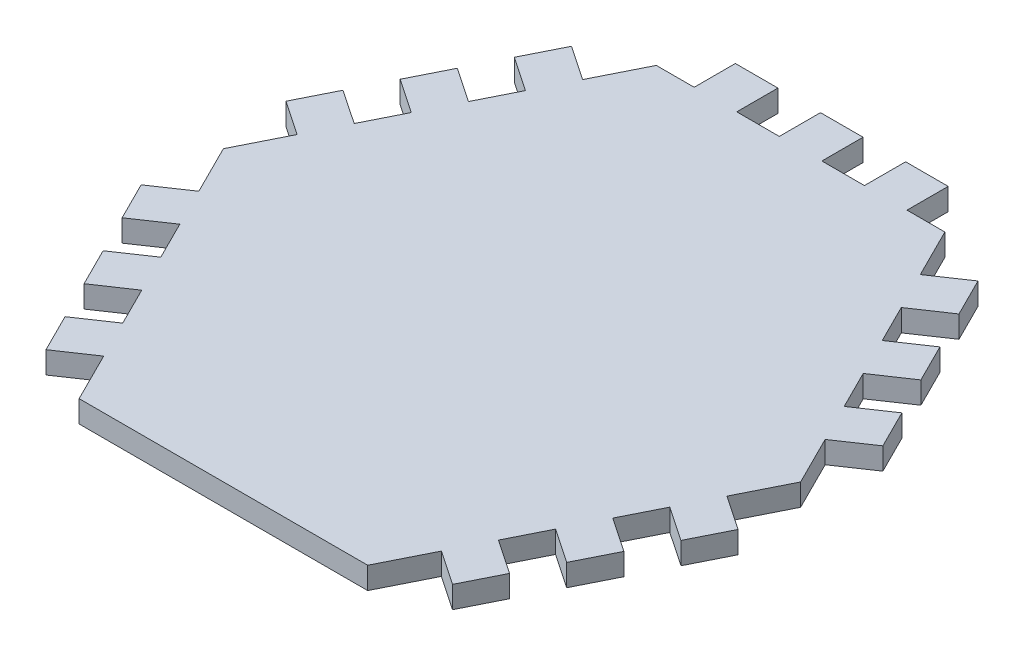
SolidWorks part; units mm, degrees
ref_plane "Front Plane" through (0, 0, 0) normal (0, 0, 1) x (1, 0, 0)
ref_plane "Top Plane" through (0, 0, 0) normal (0, 1, 0) x (1, 0, 0)
ref_plane "Right Plane" through (0, 0, 0) normal (1, 0, 0) x (0, 0, -1)
sketch "Sketch1" plane through (0, 0, 0) normal (0, 1, 0) x (1, 0, 0)
  line L0 (-36.6703, -35.293) -> (5.3697, -35.293) construction
  line L1 (5.3697, -35.293) -> (26.3947, 6.7497) construction
  line L2 (26.3947, 6.7497) -> (5.3697, 48.7923) construction
  line L3 (5.3697, 48.7923) -> (-36.6703, 48.7923) construction
  line L4 (-36.6703, 48.7923) -> (-57.6953, 6.7497) construction
  line L5 (-57.6953, 6.7497) -> (-36.6703, -35.293) construction
  line L9 (112.1005, -40.6411) -> (184.9205, -40.6411) construction
  line L10 (184.9205, -40.6411) -> (184.9205, 1.4015) construction
  line L11 (184.9205, 1.4015) -> (112.1005, -40.6411) construction
  line L12 (5.3697, -35.293) -> (8.9479, -28.1378)
  line L15 (13.961, -31.528) -> (8.9479, -28.1378)
  line L17 (11.7216, -22.5914) -> (16.7347, -25.9815)
  line L19 (19.5084, -20.435) -> (14.4953, -17.0449)
  line L21 (17.2691, -11.4984) -> (22.2821, -14.8886)
  line L23 (25.0558, -9.3421) -> (20.0428, -5.952)
  line L25 (22.8165, -0.4055) -> (27.8296, -3.7957)
  line L27 (27.8296, 17.295) -> (22.8165, 13.9048)
  line L29 (20.0428, 19.4513) -> (25.0558, 22.8414)
  line L31 (22.2821, 28.3879) -> (17.2691, 24.9978)
  line L33 (14.4953, 30.5442) -> (19.5084, 33.9344)
  line L35 (16.7347, 39.4808) -> (11.7216, 36.0907)
  line L37 (8.9479, 41.6371) -> (13.961, 45.0273)
  line L40 (-0.1469, 54.7923) -> (-0.1469, 48.7923)
  line L42 (-6.3483, 48.7923) -> (-6.3483, 54.7923)
  line L44 (-12.5496, 54.7923) -> (-12.5496, 48.7923)
  line L46 (-18.751, 48.7923) -> (-18.751, 54.7923)
  line L48 (-24.9523, 54.7923) -> (-24.9523, 48.7923)
  line L50 (-31.1537, 48.7923) -> (-31.1537, 54.7923)
  line L53 (-45.2616, 45.0273) -> (-40.2485, 41.6371)
  line L55 (-43.0222, 36.0907) -> (-48.0353, 39.4808)
  line L57 (-50.809, 33.9344) -> (-45.7959, 30.5442)
  line L59 (-48.5697, 24.9978) -> (-53.5827, 28.3879)
  line L61 (-56.3564, 22.8414) -> (-51.3434, 19.4513)
  line L63 (-54.1171, 13.9048) -> (-59.1302, 17.295)
  line L66 (-59.1302, -3.7957) -> (-54.1171, -0.4055)
  line L68 (-51.3434, -5.952) -> (-56.3564, -9.3421)
  line L70 (-53.5827, -14.8886) -> (-48.5697, -11.4984)
  line L72 (-45.7959, -17.0449) -> (-50.809, -20.435)
  line L74 (-48.0353, -25.9815) -> (-43.0222, -22.5914)
  line L76 (-40.2485, -28.1378) -> (-45.2616, -31.528)
  line L79 (13.961, -31.528) -> (16.7347, -25.9815)
  line L80 (19.5084, -20.435) -> (22.2821, -14.8886)
  line L81 (11.7216, -22.5914) -> (14.4953, -17.0449)
  line L82 (17.2691, -11.4984) -> (20.0428, -5.952)
  line L83 (25.0558, -9.3421) -> (27.8296, -3.7957)
  line L84 (22.8165, -0.4055) -> (26.3947, 6.7497)
  line L85 (26.3947, 6.7497) -> (22.8165, 13.9048)
  line L86 (27.8296, 17.295) -> (25.0558, 22.8414)
  line L87 (20.0428, 19.4513) -> (17.2691, 24.9978)
  line L88 (22.2821, 28.3879) -> (19.5084, 33.9344)
  line L89 (14.4953, 30.5442) -> (11.7216, 36.0907)
  line L90 (16.7347, 39.4808) -> (13.961, 45.0273)
  line L91 (8.9479, 41.6371) -> (5.3697, 48.7923)
  line L92 (5.3697, 48.7923) -> (-0.1469, 48.7923)
  line L93 (-0.1469, 54.7923) -> (-6.3483, 54.7923)
  line L94 (-6.3483, 48.7923) -> (-12.5496, 48.7923)
  line L95 (-12.5496, 54.7923) -> (-18.751, 54.7923)
  line L96 (-24.9523, 48.7923) -> (-18.751, 48.7923)
  line L97 (-24.9523, 54.7923) -> (-31.1537, 54.7923)
  line L98 (-31.1537, 48.7923) -> (-36.6703, 48.7923)
  line L99 (-36.6703, 48.7923) -> (-40.2485, 41.6371)
  line L100 (-45.2616, 45.0273) -> (-48.0353, 39.4808)
  line L101 (-43.0222, 36.0907) -> (-45.7959, 30.5442)
  line L102 (-50.809, 33.9344) -> (-53.5827, 28.3879)
  line L103 (-48.5697, 24.9978) -> (-51.3434, 19.4513)
  line L104 (-56.3564, 22.8414) -> (-59.1302, 17.295)
  line L105 (-54.1171, 13.9048) -> (-57.6953, 6.7497)
  line L106 (-57.6953, 6.7497) -> (-54.1171, -0.4055)
  line L107 (-59.1302, -3.7957) -> (-56.3564, -9.3421)
  line L108 (-51.3434, -5.952) -> (-48.5697, -11.4984)
  line L109 (-53.5827, -14.8886) -> (-50.809, -20.435)
  line L110 (-45.7959, -17.0449) -> (-43.0222, -22.5914)
  line L111 (-48.0353, -25.9815) -> (-45.2616, -31.528)
  line L112 (-40.2485, -28.1378) -> (-36.6703, -35.293)
  line L117 (91.1531, -75.6173) -> (59.9199, -75.6173) construction
  line L118 (59.9199, -75.6173) -> (91.1531, -57.5848) construction
  line L119 (91.1531, -57.5848) -> (91.1531, -75.6173) construction
  line L120 (59.9199, -75.6173) -> (58.3199, -72.846) construction
  line L121 (58.3199, -72.846) -> (89.5531, -54.8135) construction
  line L122 (89.5531, -54.8135) -> (91.1531, -57.5848) construction
  line L123 (59.9199, -75.6173) -> (59.9199, -71.9223) construction
  line L124 (-36.6703, -35.293) -> (5.3697, -35.293)
  line L125 (25.3619, 4.6844) -> (3.1655, 49.0694) construction
  line L126 (-34.6046, 48.7923) -> (-56.6625, 4.6844) construction
  line L127 (-37.5942, 46.9448) -> (6.2936, 46.9448) construction
  point P78 (26.4427, 20.0682)
  dimension "D1" = 42.04
  dimension "D6" = 72.82
  dimension "D7" = 30
  dimension "D8" = 84.0853
  dimension "D9" = 42.0426
  dimension "D10" = 84.0853
  dimension "D3" = 84.09
  dimension "D11" = 6.2014
  dimension "D2" = 6
  dimension "D4" = 6
  dimension "D5" = 6
  dimension "D12" = 6
  dimension "D13" = 6
  dimension "D15" = 82.5
  dimension "D16" = 82.5
  dimension "D17" = 82.5
  dimension "D18" = 82.5
  dimension "D14" = 8
  dimension "D20" = 30
  dimension "D21" = 3.2
  dimension "D22" = 1.8475
  dimension "D19" = 1.8475
  dimension "D23" = 1.8475
  dimension "D24" = 1.8475
extrude "Boss-Extrude1" add sketch "Sketch1" along normal blind 3.2
equation "\"thick\"=6"
equation "\"D10@Sketch1\"=\"D8@Sketch1\""
equation "\"D3@Sketch1\"=84.09"
equation "\"D2@Sketch1\"=\"thick\""
equation "\"D4@Sketch1\"=\"thick\""
equation "\"D5@Sketch1\"=\"thick\""
equation "\"D12@Sketch1\"=\"thick\""
equation "\"D13@Sketch1\"=\"thick\""
equation "\"D19@Sketch1\"=\"D22@Sketch1\""
equation "\"D23@Sketch1\"=\"D22@Sketch1\""
equation "\"D24@Sketch1\"=\"D22@Sketch1\""
